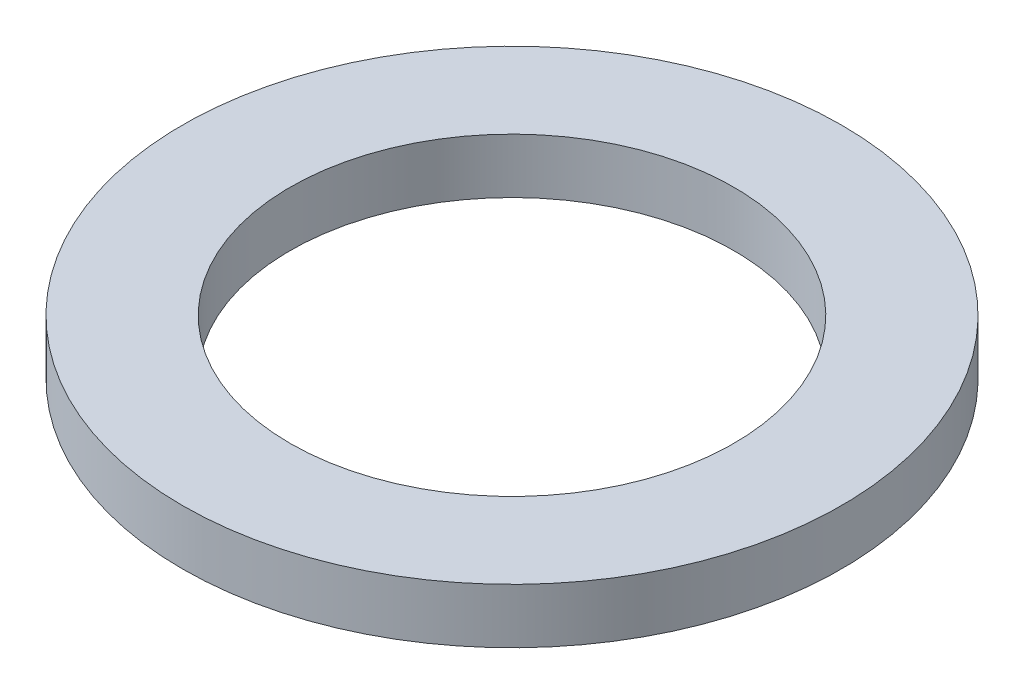
SolidWorks part; units mm, degrees
ref_plane "Front Plane" through (0, 0, 0) normal (0, 0, 1) x (1, 0, 0)
ref_plane "Top Plane" through (0, 0, 0) normal (0, 1, 0) x (1, 0, 0)
ref_plane "Right Plane" through (0, 0, 0) normal (1, 0, 0) x (0, 0, -1)
sketch "Sketch1" plane through (0, 0, 0) normal (0, 1, 0) x (1, 0, 0)
  circle A0 centre (0, 0) radius 9.525
  circle A1 centre (0, 0) radius 6.4135
  dimension "D1" = 19.05
  dimension "D2" = 12.827
extrude "Boss-Extrude1" add sketch "Sketch1" along normal blind 1.5875
